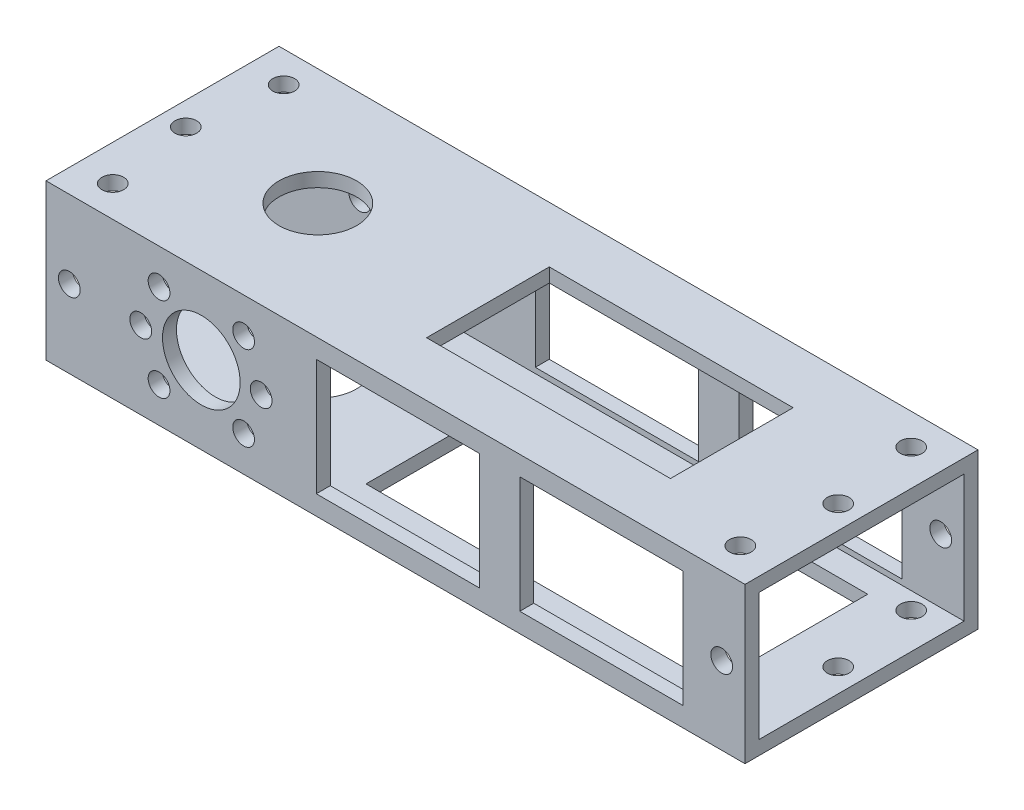
SolidWorks part; units mm, degrees
material "6061-T6 (SS)"
ref_plane "Front Plane" through (0, 0, 0) normal (0, 0, 1) x (1, 0, 0)
ref_plane "Top Plane" through (0, 0, 0) normal (0, 1, 0) x (1, 0, 0)
ref_plane "Right Plane" through (0, 0, 0) normal (1, 0, 0) x (0, 0, -1)
sketch "Sketch1" plane through (0, 0, 0) normal (0, 1, 0) x (1, 0, 0)
  line L1 (0, 0) -> (-114.3, 0)
  line L2 (0, 0) -> (0, -38.1)
  line L3 (0, -38.1) -> (-114.3, -38.1)
  line L4 (-114.3, 0) -> (-114.3, -38.1)
  dimension "D1" = 114.3
  dimension "D2" = 38.1
extrude "Boss-Extrude1" add sketch "Sketch1" along normal blind 25.4
sketch "Sketch2" plane through (0, 0, 0) normal (1, 0, 0) x (0, 0, -1)
  line L0 (0, 0) -> (-2.286, 0) construction
  line L1 (-38.1, 0) -> (0, 0) construction
  line L2 (-2.286, 0) -> (-2.286, 2.286) construction
  line L4 (-2.286, 2.286) -> (-35.814, 2.286)
  line L5 (-2.286, 2.286) -> (-2.286, 23.114)
  line L6 (-2.286, 23.114) -> (-35.814, 23.114)
  line L7 (-35.814, 2.286) -> (-35.814, 23.114)
  line L8 (-38.1, 25.4) -> (-38.1, 0) construction
  point P11 (-38.1, 12.7)
  dimension "D1" = 20.828
  dimension "D2" = 33.528
  dimension "D3" = 2.286
  dimension "D4" = 2.286
extrude "Cut-Extrude1" cut sketch "Sketch2" against normal up to next
sketch "Sketch4" plane through (0, 0, 0) normal (0, 0, -1) x (-1, 0, 0)
  line L0 (0, 0) -> (0, 12.7) construction
  line L1 (0, 25.4) -> (0, 0) construction
  line L2 (0, 12.7) -> (3.81, 12.7) construction
  circle A0 centre (3.81, 12.7) radius 1.778
  dimension "D1" = 3.556
  dimension "D2" = 3.81
extrude "Cut-Extrude3" cut sketch "Sketch4" against normal up to surface (38.1 mm away) up to face at (-57.15, 12.7, 38.1)
sketch "Sketch6" plane through (0, 0, 0) normal (0, 0, -1) x (-1, 0, 0)
  line L0 (114.3, 0) -> (114.3, 12.7) construction
  line L1 (114.3, 25.4) -> (114.3, 0) construction
  line L2 (114.3, 12.7) -> (110.49, 12.7) construction
  line L3 (114.3, 12.7) -> (88.9, 12.7) construction
  line L4 (88.9, 12.7) -> (81.9852, 5.7852) construction
  line L5 (88.9, 12.7) -> (95.8148, 19.6148) construction
  line L6 (88.9, 12.7) -> (95.8148, 5.7852) construction
  line L7 (88.9, 12.7) -> (81.9852, 19.6148) construction
  line L8 (0, 12.7) -> (43.434, 12.7) construction
  line L9 (88.9, 12.7) -> (98.806, 12.7) construction
  line L10 (88.9, 12.7) -> (79.121, 12.7) construction
  line L11 (0, 12.7) -> (10.16, 12.7) construction
  line L12 (0, 25.4) -> (0, 0) construction
  line L13 (10.16, 12.7) -> (10.16, 22.225)
  line L14 (10.16, 22.225) -> (36.83, 22.225)
  line L15 (36.83, 22.225) -> (36.83, 3.175)
  line L16 (36.83, 3.175) -> (10.16, 3.175)
  line L17 (10.16, 3.175) -> (10.16, 12.7)
  line L18 (0, 25.4) -> (114.3, 25.4) construction
  line L19 (43.434, 12.7) -> (43.434, 22.225)
  line L20 (43.434, 22.225) -> (70.104, 22.225)
  line L21 (70.104, 22.225) -> (70.104, 3.175)
  line L22 (70.104, 3.175) -> (43.434, 3.175)
  line L23 (43.434, 3.175) -> (43.434, 12.7)
  circle A0 centre (110.49, 12.7) radius 1.778
  circle A1 centre (88.9, 12.7) radius 6.35
  circle A2 centre (81.9852, 19.6148) radius 1.778
  circle A3 centre (95.8148, 19.6148) radius 1.778
  circle A4 centre (95.8148, 5.7852) radius 1.778
  circle A5 centre (81.9852, 5.7852) radius 1.778
  circle A6 centre (79.121, 12.7) radius 1.778
  circle A7 centre (98.806, 12.7) radius 1.778
  dimension "D1" = 12.7
  dimension "D2" = 3.81
  dimension "D3" = 3.556
  dimension "D5" = 9.779
  dimension "D7" = 9.906
  dimension "D4" = 25.4
  dimension "D6" = 32.3148
  dimension "D8" = 10.16
  dimension "D9" = 26.67
  dimension "D10" = 3.175
  dimension "D11" = 19.05
  dimension "D12" = 43.434
extrude "Cut-Extrude5" cut sketch "Sketch6" against normal up to surface (38.1 mm away) up to face at (-5.588, 12.7, 38.1)
sketch "Sketch7" plane through (0, 25.4, 0) normal (0, 1, 0) x (1, 0, 0)
  line L0 (-114.3, -38.1) -> (-114.3, -19.05) construction
  line L1 (-114.3, 0) -> (-114.3, -38.1) construction
  line L2 (-114.3, -19.05) -> (-110.49, -19.05) construction
  line L3 (-114.3, -19.05) -> (-88.9, -19.05) construction
  line L4 (-88.9, -19.05) -> (-60.96, -19.05) construction
  line L5 (-60.96, -19.05) -> (-60.96, -9.144)
  line L6 (-60.96, -19.05) -> (-60.96, -29.21)
  line L7 (-60.96, -29.21) -> (-21.082, -29.21)
  line L8 (-60.96, -9.144) -> (-21.082, -9.144)
  line L9 (-21.082, -9.144) -> (-21.082, -29.21)
  line L10 (0, -38.1) -> (0, 0) construction
  line L12 (-41.021, -29.21) -> (-41.021, -38.1) construction
  line L13 (-114.3, -38.1) -> (0, -38.1) construction
  line L14 (-114.3, 0) -> (-108.458, 0) construction
  line L15 (0, 0) -> (-114.3, 0) construction
  line L16 (-108.458, 0) -> (-108.458, -5.08) construction
  line L17 (-114.3, -38.1) -> (-108.458, -38.1) construction
  line L18 (-108.458, -38.1) -> (-108.458, -33.02) construction
  circle A0 centre (-110.49, -19.05) radius 1.778
  circle A1 centre (-88.9, -19.05) radius 6.35
  circle A2 centre (-108.458, -5.08) radius 1.778
  circle A3 centre (-108.458, -33.02) radius 1.778
  dimension "D1" = 12.7
  dimension "D3" = 3.556
  dimension "D2" = 3.81
  dimension "D4" = 25.4
  dimension "D5" = 20.066
  dimension "D6" = 39.878
  dimension "D7" = 21.082
  dimension "D8" = 8.89
  dimension "D9" = 5.842
  dimension "D10" = 5.08
extrude "Cut-Extrude6" cut sketch "Sketch7" against normal up to next
sketch "Sketch8" plane through (0, 0, 0) normal (0, -1, 0) x (1, 0, 0)
  line L0 (-114.3, 38.1) -> (-114.3, 19.05) construction
  line L1 (-114.3, 0) -> (-114.3, 38.1) construction
  line L2 (-114.3, 19.05) -> (-110.49, 19.05) construction
  line L3 (-114.3, 19.05) -> (-88.9, 19.05) construction
  line L4 (-88.9, 19.05) -> (-68.326, 19.05) construction
  line L5 (-68.326, 19.05) -> (-68.326, 31.75)
  line L6 (-68.326, 19.05) -> (-68.326, 6.35)
  line L7 (-68.326, 31.75) -> (-11.684, 31.75)
  line L8 (-68.326, 6.35) -> (-11.684, 6.35)
  line L9 (-11.684, 6.35) -> (-11.684, 31.75)
  line L10 (-114.3, 0) -> (-108.458, 0) construction
  line L11 (0, 0) -> (-114.3, 0) construction
  line L12 (-114.3, 38.1) -> (0, 38.1) construction
  line L13 (-40.005, 31.75) -> (-40.005, 38.1) construction
  line L14 (-68.326, 19.05) -> (-68.326, 38.1) construction
  line L15 (-108.458, 0) -> (-108.458, 5.08) construction
  line L16 (-114.3, 38.1) -> (-108.458, 38.1) construction
  line L17 (-108.458, 38.1) -> (-108.458, 33.02) construction
  circle A0 centre (-110.49, 19.05) radius 1.778
  circle A1 centre (-88.9, 19.05) radius 6.35
  circle A2 centre (-108.458, 33.02) radius 1.778
  circle A3 centre (-108.458, 5.08) radius 1.778
  dimension "D1" = 12.7
  dimension "D4" = 3.556
  dimension "D8" = 20.574
  dimension "D2" = 56.642
  dimension "D3" = 25.4
  dimension "D5" = 3.81
  dimension "D6" = 25.4
  dimension "D7" = 6.35
  dimension "D9" = 19.05
  dimension "D10" = 5.842
  dimension "D11" = 5.08
extrude "Cut-Extrude7" cut sketch "Sketch8" against normal up to next
sketch "Sketch10" plane through (0, 0, 0) normal (0, -1, 0) x (-1, 0, 0)
  line L0 (0, -38.1) -> (0, -19.05) construction
  line L1 (0, -38.1) -> (0, 0) construction
  line L2 (0, -19.05) -> (3.81, -19.05) construction
  line L3 (0, -38.1) -> (5.842, -38.1) construction
  line L4 (114.3, -38.1) -> (0, -38.1) construction
  line L5 (5.842, -38.1) -> (5.842, -33.02) construction
  line L6 (0, 0) -> (5.842, 0) construction
  line L7 (0, 0) -> (114.3, 0) construction
  line L8 (5.842, 0) -> (5.842, -5.08) construction
  circle A0 centre (3.81, -19.05) radius 1.778
  circle A1 centre (5.842, -33.02) radius 1.778
  circle A2 centre (5.842, -5.08) radius 1.778
  dimension "D1" = 3.556
  dimension "D3" = 5.842
  dimension "D2" = 5.08
  dimension "D4" = 3.81
extrude "Cut-Extrude9" cut sketch "Sketch10" against normal up to surface (25.4 mm away) up to face at (-108.458, 25.4, 34.798)
